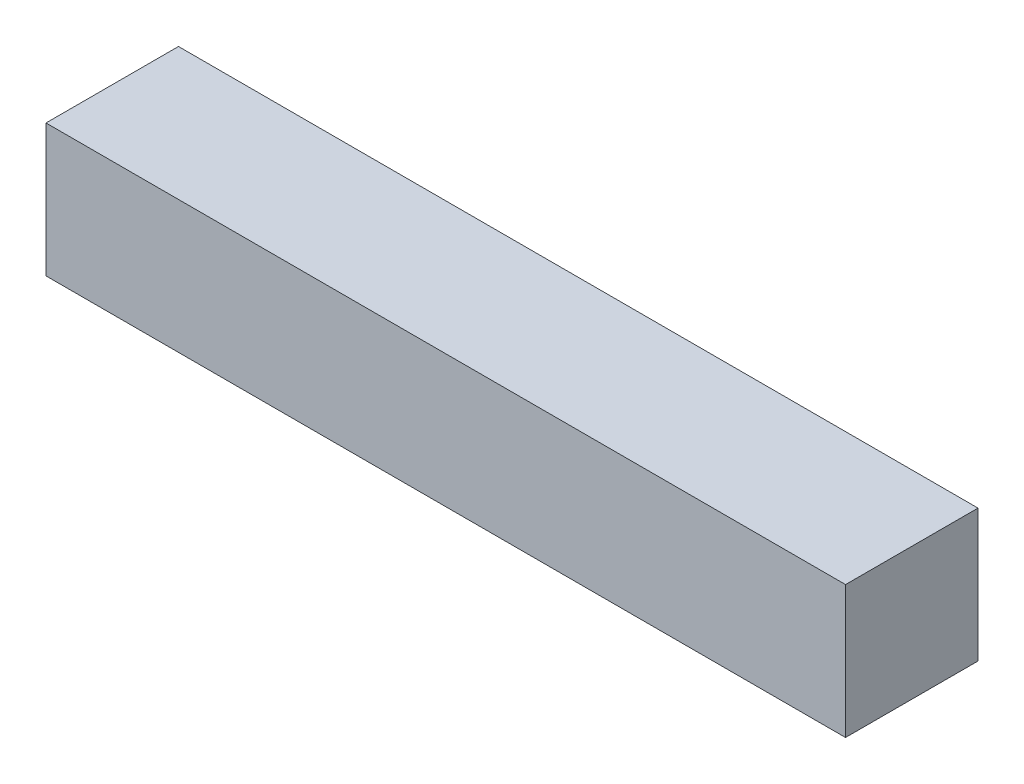
SolidWorks part; units mm, degrees
ref_plane "Front Plane" through (0, 0, 0) normal (0, 0, 1) x (1, 0, 0)
ref_plane "Top Plane" through (0, 0, 0) normal (0, 1, 0) x (1, 0, 0)
ref_plane "Right Plane" through (0, 0, 0) normal (1, 0, 0) x (0, 0, -1)
sketch "Sketch1" plane through (0, 0, 0) normal (1, 0, 0) x (0, 0, -1)
  line L1 (-14, -14) -> (14, -14)
  line L2 (-14, -14) -> (-14, 14)
  line L3 (-14, 14) -> (14, 14)
  line L4 (14, -14) -> (14, 14)
  line L5 (-14, -14) -> (14, 14) construction
  line L6 (-14, 14) -> (14, -14) construction
  point P0 (0, 0)
  dimension "D1" = 28
  dimension "D2" = 28
extrude "Boss-Extrude1" add sketch "Sketch1" along normal blind 169
